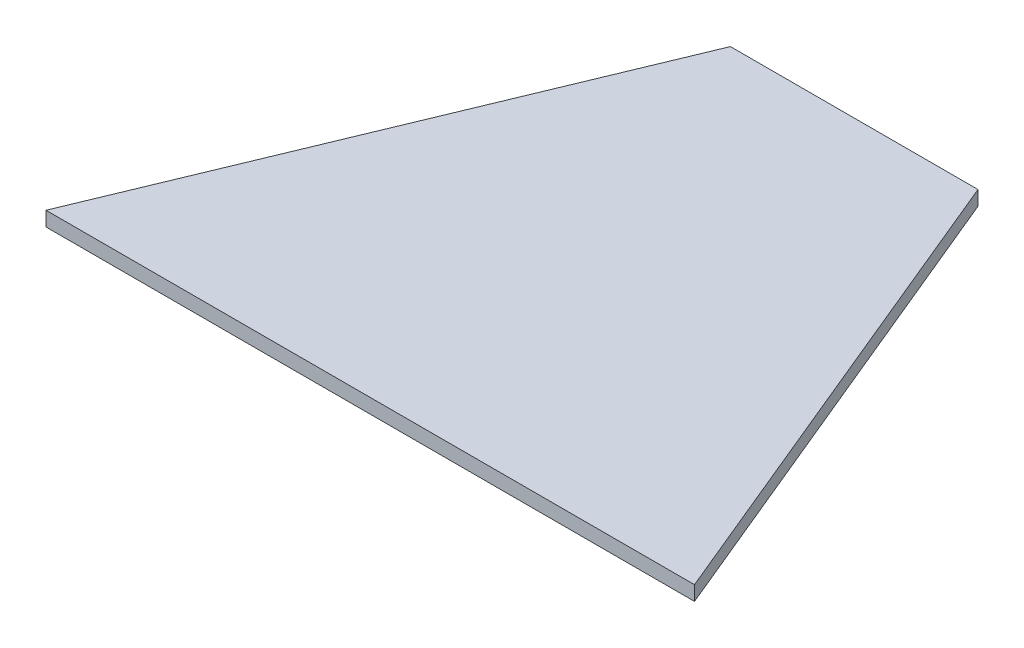
SolidWorks part; units mm, degrees
ref_plane "Front Plane" through (0, 0, 0) normal (0, 0, 1) x (1, 0, 0)
ref_plane "Top Plane" through (0, 0, 0) normal (0, 1, 0) x (1, 0, 0)
ref_plane "Right Plane" through (0, 0, 0) normal (1, 0, 0) x (0, 0, -1)
sketch "Sketch1" plane through (0, 0, 0) normal (0, 1, 0) x (1, 0, 0)
  line L0 (0, 0) -> (134, 0)
  line L1 (0, 0) -> (41.4214, 100)
  line L2 (134, 0) -> (92.5786, 100)
  line L3 (67, 0) -> (67, 100) construction
  line L4 (41.4214, 100) -> (92.5786, 100)
  point P4 (92.5786, 100.5956)
  point P9 (0, 0)
  point P10 (0, 0)
  point P11 (0, 0)
  point P12 (0, 0)
  point P13 (41.4214, 100.4751)
extrude "Boss-Extrude1" add sketch "Sketch1" along normal blind 3
